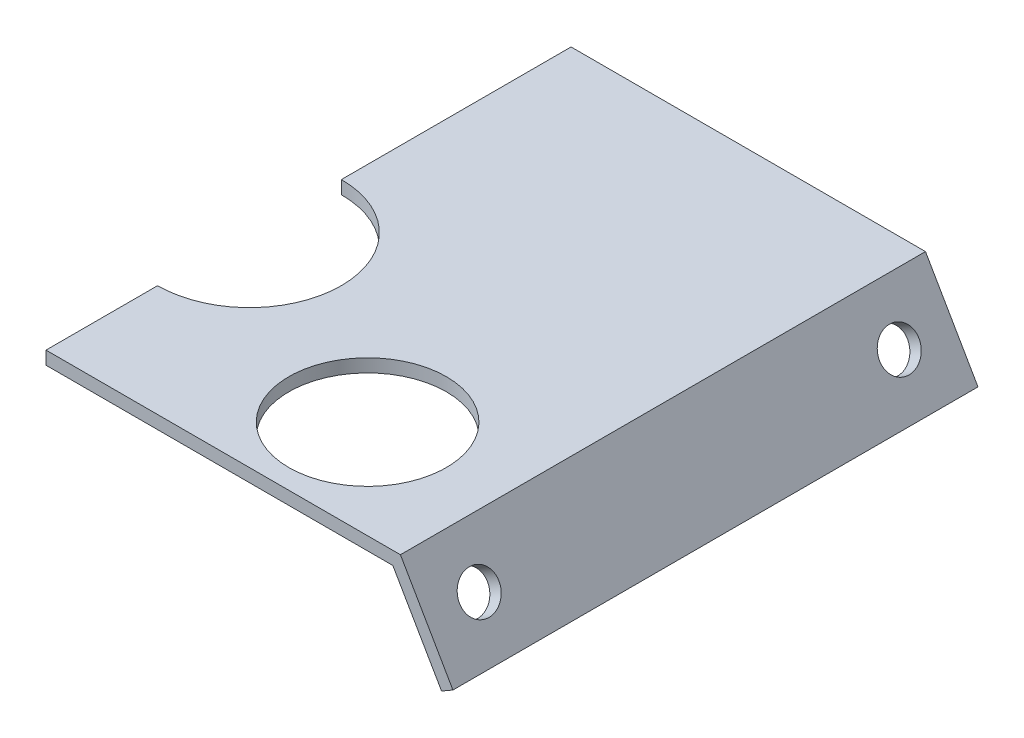
SolidWorks part; units mm, degrees
ref_plane "Front Plane" through (0, 0, 0) normal (0, 0, 1) x (1, 0, 0)
ref_plane "Top Plane" through (0, 0, 0) normal (0, 1, 0) x (1, 0, 0)
ref_plane "Right Plane" through (0, 0, 0) normal (1, 0, 0) x (0, 0, -1)
sketch "Sketch1" plane through (0, 0, 0) normal (0, 0, 1) x (1, 0, 0)
  line L0 (0, 0) -> (27, 0)
  line L1 (27, 0) -> (31, -6.9282)
  line L2 (0, -1) -> (26.4226, -1)
  line L3 (26.4226, -1) -> (30.134, -7.4282)
  line L4 (31, -6.9282) -> (30.134, -7.4282)
  line L5 (0, 0) -> (0, -1)
  dimension "D1" = 1
extrude "Boss-Extrude1" add sketch "Sketch1" along normal blind 40
sketch "Sketch2" plane through (20.25, 11.6913, 0) normal (0.866, 0.5, 0) x (0, 0, -1)
  line L0 (-40, -21.5) -> (-40, -13.5) construction
  line L1 (0, -21.5) -> (0, -13.5) construction
  circle A0 centre (-36, -17.5) radius 1.5
  circle A1 centre (-4, -17.5) radius 1.5
  point P4 (-40, -17.5)
  dimension "D1" = 4
  dimension "D2" = 4
extrude "Cut-Extrude1" cut sketch "Sketch2" against normal blind 40
sketch "Sketch3" plane through (0, 0, 0) normal (0, 1, 0) x (-1, 0, 0)
  line L0 (0, 40) -> (0, 0) construction
  line L1 (-27, 40) -> (0, 40) construction
  circle A0 centre (0, 24.5) radius 7
  circle A1 centre (-17, 32.5) radius 6
  dimension "D1" = 15.5
  dimension "D2" = 17
  dimension "D3" = 7.5
extrude "Cut-Extrude2" cut sketch "Sketch3" against normal blind 40
